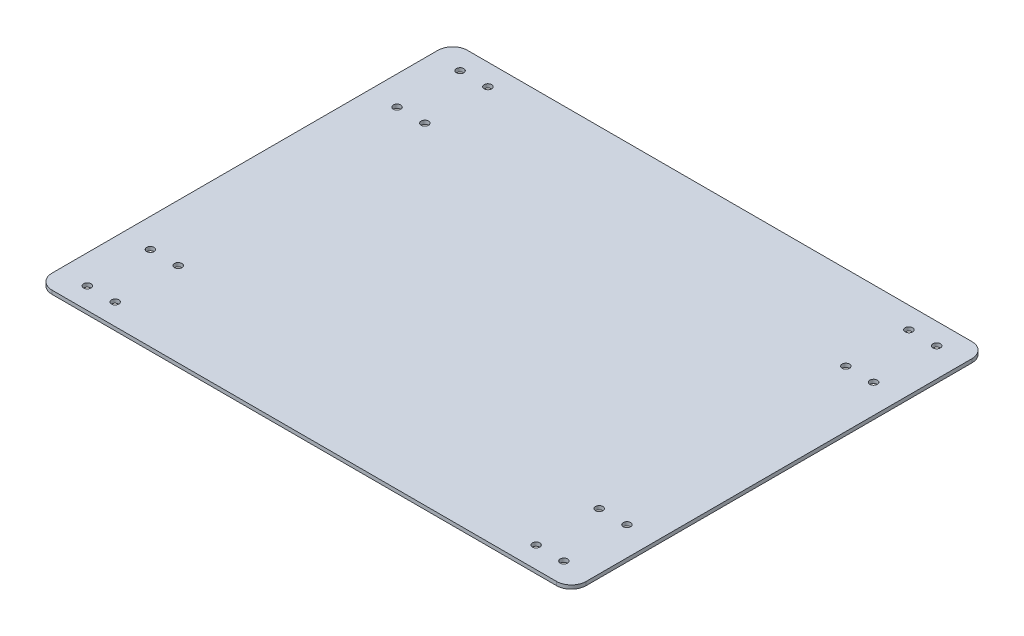
SolidWorks part; units mm, degrees
material "6061-O (SS)"
ref_plane "Front Plane" through (0, 0, 0) normal (0, 0, 1) x (1, 0, 0)
ref_plane "Top Plane" through (0, 0, 0) normal (0, 1, 0) x (1, 0, 0)
ref_plane "Right Plane" through (0, 0, 0) normal (1, 0, 0) x (0, 0, -1)
sketch "Sketch1" plane through (0, 0, 0) normal (0, 1, 0) x (1, 0, 0)
  line L1 (-228.6, -177.8) -> (228.6, -177.8)
  line L2 (-228.6, -177.8) -> (-228.6, 177.8)
  line L3 (-228.6, 177.8) -> (228.6, 177.8)
  line L4 (228.6, -177.8) -> (228.6, 177.8)
  line L5 (-228.6, -177.8) -> (228.6, 177.8) construction
  line L6 (-228.6, 177.8) -> (228.6, -177.8) construction
  point P0 (0, 0)
  dimension "D1" = 355.6
  dimension "D2" = 457.2
extrude "Boss-Extrude1" add sketch "Sketch1" along normal blind 3.175 contours L3 L4 L1 L2
fillet "Fillet1" radius 12.7 4 edges at (-228.6, 1.5875, -177.8) (228.6, 1.5875, -177.8) (228.6, 1.5875, 177.8) (-228.6, 1.5875, 177.8)
sketch "Sketch3" plane through (0, 0, 0) normal (0, -1, 0) x (1, 0, 0)
  circle A0 centre (180.1813, -159.5437) radius 3.175 construction
  circle A1 centre (180.1813, -105.5688) radius 3.175 construction
  circle A2 centre (203.9938, -159.5437) radius 3.175 construction
  circle A3 centre (203.9938, -105.5688) radius 3.175 construction
  circle A4 centre (180.1813, -159.5437) radius 3.175
  circle A5 centre (180.1813, -105.5688) radius 3.175
  circle A6 centre (203.9938, -159.5437) radius 3.175
  circle A7 centre (203.9938, -105.5688) radius 3.175
extrude "Cut-Extrude1" cut sketch "Sketch3" against normal through all
mirror "Mirror1" about plane through (0, 0, 0) normal (0, 0, 1) of "Cut-Extrude1"
mirror "Mirror2" about plane through (0, 0, 0) normal (1, 0, 0) of "Mirror1", "Cut-Extrude1"
